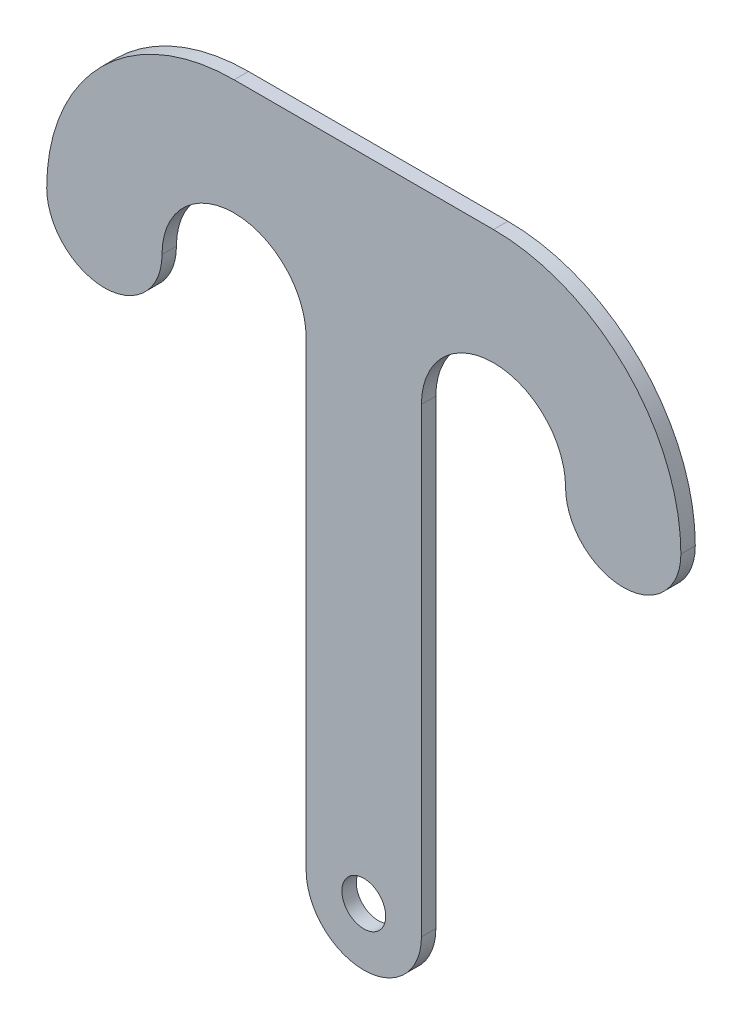
SolidWorks part; units mm, degrees
ref_plane "Front Plane" through (0, 0, 0) normal (0, 0, 1) x (1, 0, 0)
ref_plane "Top Plane" through (0, 0, 0) normal (0, 1, 0) x (1, 0, 0)
ref_plane "Right Plane" through (0, 0, 0) normal (1, 0, 0) x (0, 0, -1)
sketch "Sketch1" plane through (0, 0, 0) normal (0, 0, 1) x (1, 0, 0)
  line L0 (12.7, 0) -> (12.7, 101.6)
  line L1 (-12.7, 0) -> (-12.7, 101.6)
  line L2 (0, 0) -> (0, 79.2928) construction
  line L3 (28.575, 142.875) -> (-28.575, 142.875)
  circle A0 centre (0, 0) radius 4.826
  arc A2 (-12.7, 0) -> (12.7, 0) centre (0, 0) ccw
  arc A3 (12.7, 101.6) -> (44.45, 101.6) centre (28.575, 101.6) cw
  arc A4 (44.45, 101.6) -> (69.85, 101.6) centre (57.15, 101.6) ccw
  arc A7 (69.85, 101.6) -> (28.575, 142.875) centre (28.575, 101.6) ccw
  arc A8 (-69.85, 101.6) -> (-28.575, 142.875) centre (-28.575, 101.6) cw
  arc A9 (-44.45, 101.6) -> (-69.85, 101.6) centre (-57.15, 101.6) cw
  arc A10 (-12.7, 101.6) -> (-44.45, 101.6) centre (-28.575, 101.6) ccw
  point P20 (-30.1784, 149.1438)
  point P21 (66.2642, 84.773)
  point P22 (-14.2118, 149.4056)
  point P23 (0, 0)
  dimension "D1" = 25.4
  dimension "D4" = 41.275
  dimension "D2" = 15.875
  dimension "D5" = 9.652
  dimension "D3" = 101.6
extrude "Boss-Extrude2" add sketch "Sketch1" along normal blind 3.175
